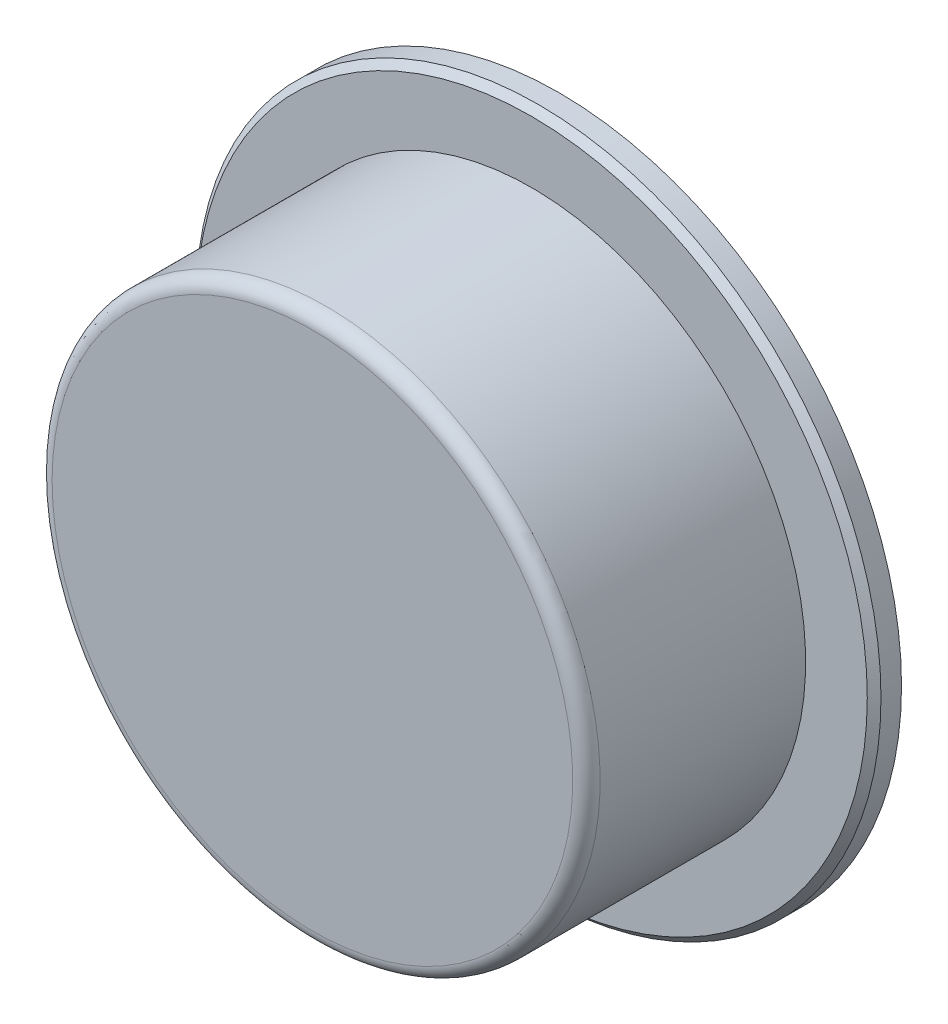
SolidWorks part; units mm, degrees
ref_plane "Plan de face" through (0, 0, 0) normal (0, 0, 1) x (1, 0, 0)
ref_plane "Plan de dessus" through (0, 0, 0) normal (0, 1, 0) x (1, 0, 0)
ref_plane "Plan de droite" through (0, 0, 0) normal (1, 0, 0) x (0, 0, -1)
ref_plane "Plan1" through (0, 0, 0) normal (0, -1, 0) x (1, 0, 0)
sketch "Esquisse1" plane through (0, 0, 0) normal (0, -1, 0) x (1, 0, 0)
  line L0 (3.8, 3.6) -> (0, 3.6)
  line L1 (0, 3.6) -> (0, 0)
  line L4 (0, 0) -> (5, 0)
  line L5 (5, 0) -> (5, 0.4)
  line L6 (5, 0.4) -> (4, 0.4)
  line L7 (4, 0.4) -> (4, 3.4)
  arc A0 (4, 3.4) -> (3.8, 3.6) centre (3.8, 3.4) ccw
  dimension "D3" = 0.2
  dimension "D1" = 3.6
  dimension "D2" = 3.8
  dimension "D4" = 0.4
  dimension "D5" = 5
  dimension "D6" = 4
revolve "Révolution1" add sketch "Esquisse1" angle 360 about L1
chamfer "Chanfrein1" distance 0.1 angle 45 1 edges at (-5, 0, 0.4)
